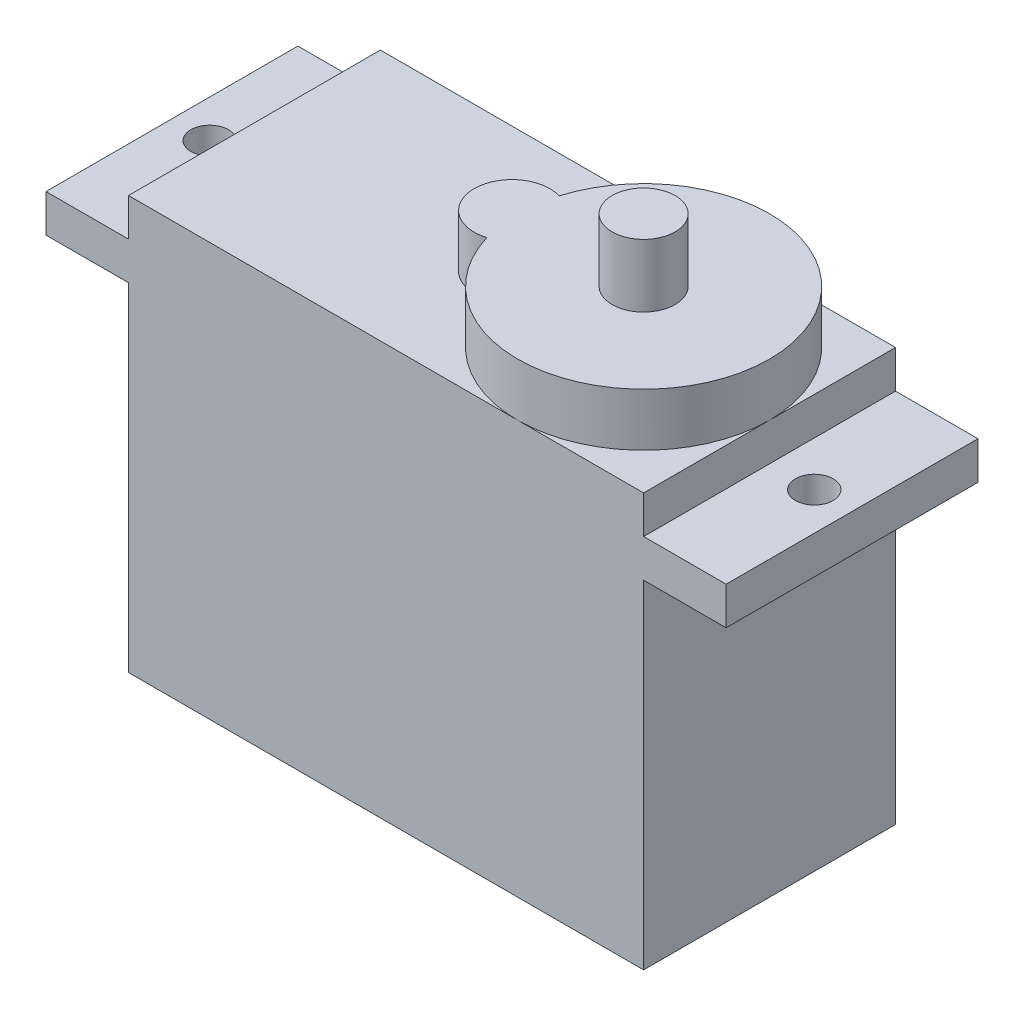
SolidWorks part; units mm, degrees
ref_plane "Front Plane" through (0, 0, 0) normal (0, 0, 1) x (1, 0, 0)
ref_plane "Top Plane" through (0, 0, 0) normal (0, 1, 0) x (1, 0, 0)
ref_plane "Right Plane" through (0, 0, 0) normal (1, 0, 0) x (0, 0, -1)
sketch "Sketch1" plane through (0, 0, 0) normal (0, 0, 1) x (1, 0, 0)
  line L1 (-20.45, 13.4) -> (20.45, 13.4)
  line L2 (-20.45, 13.4) -> (-20.45, -13.4)
  line L3 (-20.45, -13.4) -> (20.45, -13.4)
  line L4 (20.45, 13.4) -> (20.45, -13.4)
  line L5 (-20.45, 13.4) -> (20.45, -13.4) construction
  line L6 (-20.45, -13.4) -> (20.45, 13.4) construction
  point P0 (0, 0)
  dimension "D1" = 40.9
  dimension "D2" = 26.8
extrude "Boss-Extrude1" add sketch "Sketch1" along normal mid plane 20
sketch "Sketch2" plane through (0, 13.4, 0) normal (0, 1, 0) x (1, 0, 0)
  line L1 (-27, 10) -> (27, 10)
  line L2 (-27, 10) -> (-27, -10)
  line L3 (-27, -10) -> (27, -10)
  line L4 (27, 10) -> (27, -10)
  line L5 (-27, 10) -> (27, -10) construction
  line L6 (-27, -10) -> (27, 10) construction
  point P0 (0, 0)
  dimension "D1" = 20
  dimension "D2" = 54
extrude "Boss-Extrude2" add sketch "Sketch2" along normal blind 3
sketch "Sketch3" plane through (0, 16.4, 0) normal (0, 1, 0) x (1, 0, 0)
  line L0 (-27, 10) -> (-27, -10) construction
  line L1 (27, -10) -> (27, 10) construction
  circle A0 centre (-24, 0) radius 1.5
  circle A1 centre (24, 0) radius 1.5
  dimension "D1" = 3
  dimension "D2" = 3
  dimension "D3" = 3
  dimension "D4" = 3
extrude "Cut-Extrude1" cut sketch "Sketch3" against normal blind 3
sketch "Sketch4" plane through (0, 16.4, 0) normal (0, 1, 0) x (1, 0, 0)
  line L0 (-27, -10) -> (27, -10) construction
  line L1 (-20.45, 10) -> (20.45, 10)
  line L2 (-20.45, 10) -> (-20.45, -10)
  line L3 (-20.45, -10) -> (20.45, -10)
  line L4 (20.45, 10) -> (20.45, -10)
  line L5 (-20.45, 10) -> (20.45, -10) construction
  line L6 (-20.45, -10) -> (20.45, 10) construction
  point P0 (0, 0)
  dimension "D1" = 40.9
extrude "Boss-Extrude3" add sketch "Sketch4" along normal blind 3
sketch "Sketch5" plane through (0, 19.4, 0) normal (0, 1, 0) x (1, 0, 0)
  line L0 (20.45, -10) -> (20.45, 10) construction
  arc A0 (0.8709, -2.8708) -> (0.8709, 2.8708) centre (10.45, 0) ccw
  arc A1 (0.8709, 2.8708) -> (0.8709, -2.8708) centre (0, 0) ccw
  dimension "D1" = 20
  dimension "D3" = 6
  dimension "D2" = 10
extrude "Boss-Extrude4" add sketch "Sketch5" along normal blind 4.2
sketch "Sketch6" plane through (0, 23.6, 0) normal (0, 1, 0) x (1, 0, 0)
  line L0 (20.45, -10) -> (20.45, 0) construction
  circle A0 centre (10.45, 0) radius 2.5
  dimension "D2" = 5
  dimension "D1" = 10
extrude "Boss-Extrude5" add sketch "Sketch6" along normal blind 5
